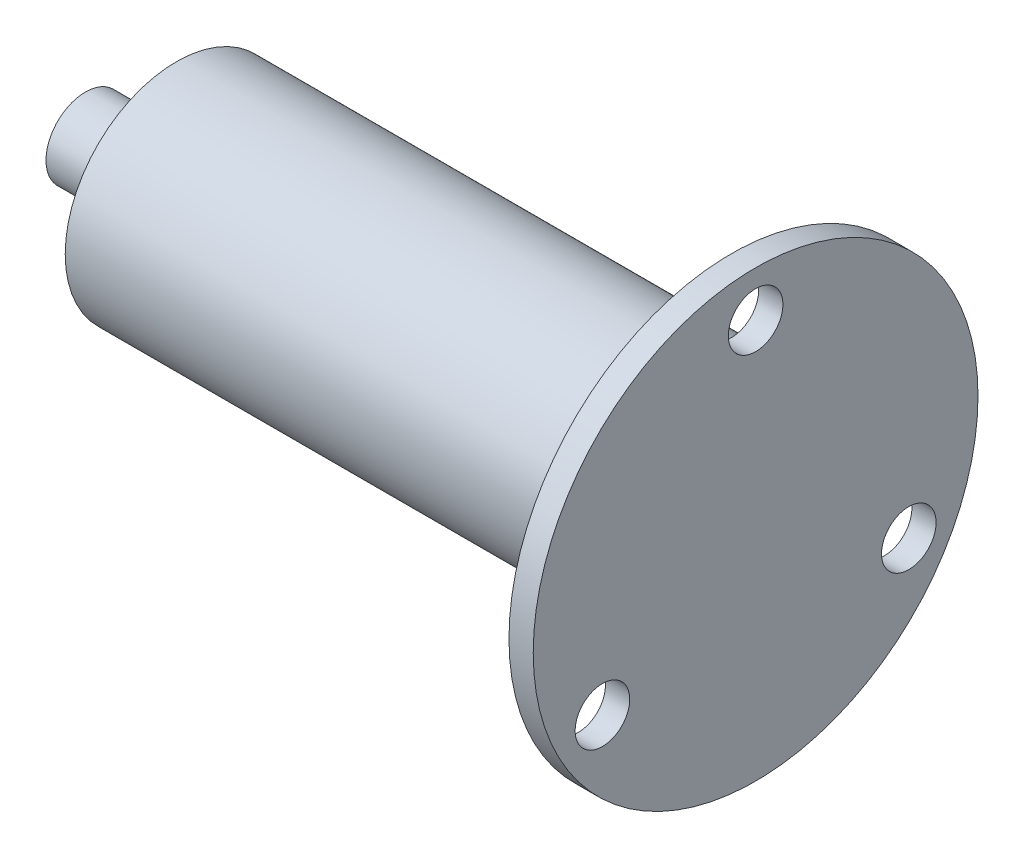
SolidWorks part; units mm, degrees
ref_plane "前视基准面" through (0, 0, 0) normal (0, 0, 1) x (1, 0, 0)
ref_plane "上视基准面" through (0, 0, 0) normal (0, 1, 0) x (1, 0, 0)
ref_plane "右视基准面" through (0, 0, 0) normal (1, 0, 0) x (0, 0, -1)
other "Configuration Table"
sketch "草图1" plane through (0, 0, 0) normal (0, 0, 1) x (1, 0, 0)
  line L0 (0, 0) -> (17124.3976, 0) construction
  line L1 (0, 0) -> (0, 3.9)
  line L2 (0, 3.9) -> (9, 3.9)
  line L3 (9, 3.9) -> (9, 11)
  line L4 (9, 11) -> (63.9, 11)
  line L5 (63.9, 11) -> (63.9, 22)
  line L6 (63.9, 22) -> (66.3, 22)
  line L7 (66.3, 22) -> (66.3, 11)
  line L9 (66.3, 11) -> (66.3, 0)
  line L10 (66.3, 0) -> (0, 0)
  point P9 (63.9, 10.2198)
  point P13 (18.6484, 11)
  point P14 (65.0173, 11)
  point P15 (66.4417, 11)
  dimension "D1" = 3.9
  dimension "D2" = 9
  dimension "D3" = 2.4
  dimension "D4" = 11
  dimension "D5" = 57.3
  dimension "D7" = 22
revolve "旋转1" add sketch "草图1" angle 360 about L0
sketch "草图2" plane through (63.9, 0, 0) normal (-1, 0, 0) x (0, 0, 1)
  circle A0 centre (0, 0) radius 17.5 construction
  circle A1 centre (0, 17.5) radius 2.7
  circle A2 centre (15.1554, -8.75) radius 2.7
  circle A3 centre (-15.1554, -8.75) radius 2.7
  point P12 (0, 0)
  dimension "D1" = 35
  dimension "D2" = 5.4
  dimension "D3" = 3
extrude "切除-拉伸1" cut sketch "草图2" against normal blind 10
